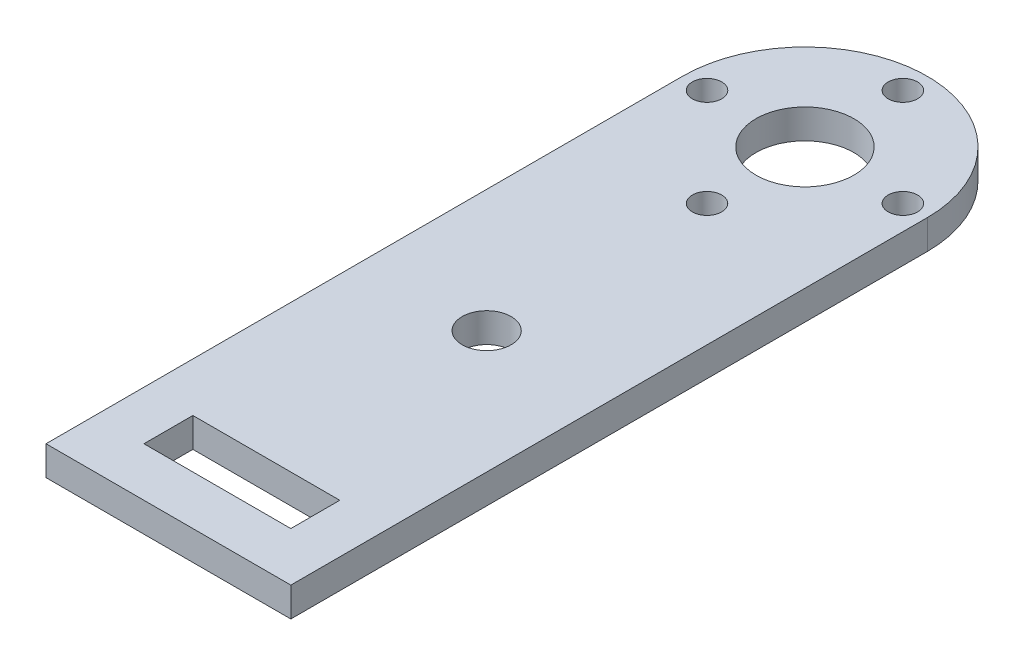
SolidWorks part; units mm, degrees
ref_plane "Front Plane" through (0, 0, 0) normal (0, 0, 1) x (1, 0, 0)
ref_plane "Top Plane" through (0, 0, 0) normal (0, 1, 0) x (1, 0, 0)
ref_plane "Right Plane" through (0, 0, 0) normal (1, 0, 0) x (0, 0, -1)
sketch "Sketch1" plane through (0, 0, 0) normal (0, 1, 0) x (1, 0, 0)
  line L0 (1.25, 0) -> (1.25, 0.75) construction
  line L1 (0, 0) -> (2.5, 0)
  line L2 (0, 0) -> (0, 6.5)
  line L4 (2.5, 0) -> (2.5, 6.5)
  line L5 (2, 0.5) -> (0.5, 0.5)
  line L6 (2, 0.5) -> (2, 1)
  line L7 (2, 1) -> (0.5, 1)
  line L8 (0.5, 0.5) -> (0.5, 1)
  line L9 (2, 0.5) -> (0.5, 1) construction
  line L10 (2, 1) -> (0.5, 0.5) construction
  arc A0 (0, 6.5) -> (2.5, 6.5) centre (1.25, 6.5) cw
  circle A1 centre (1.25, 6.5) radius 0.5
  point P9 (1.3315, 1.142)
  point P12 (1.25, 0.75)
  dimension "D3" = 1
  dimension "D6" = 1.5
  dimension "D1" = 2.5
  dimension "D2" = 6.5
  dimension "D4" = 0.75
  dimension "D5" = 0.5
extrude "Boss-Extrude1" add sketch "Sketch1" along normal blind 0.3
sketch "Sketch2" plane through (0, 0.3, 0) normal (0, 1, 0) x (1, 0, 0)
  circle A0 centre (1.25, 6.5) radius 1
  circle A1 centre (0.25, 6.5) radius 0.15
  dimension "D1" = 2
  dimension "D2" = 0.3
extrude "Cut-Extrude1" cut sketch "Sketch2" against normal blind 0.3 contours A1
pattern_circular "CirPattern1" count 4 every 90 about axis through (1.25, 0, -6.5) along (0, 1, 0) of "Cut-Extrude1"
sketch "Sketch5" plane through (0, 0.3, 0) normal (0, 1, 0) x (1, 0, 0)
  circle A0 centre (1.25, 3.25) radius 0.25
  dimension "D1" = 0.5
extrude "Cut-Extrude3" cut sketch "Sketch5" against normal blind 0.3
